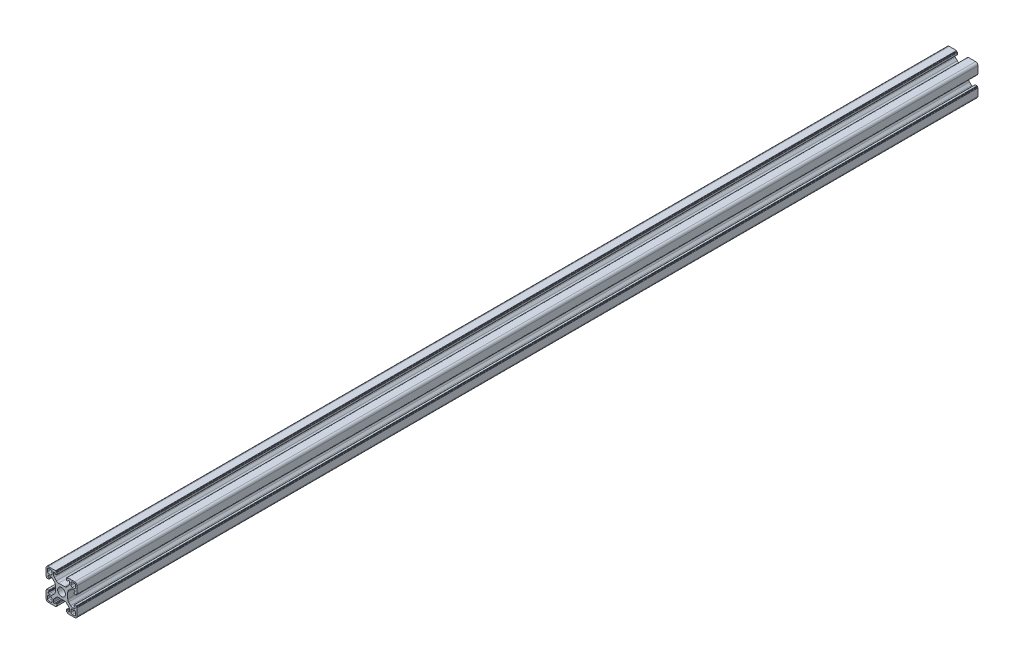
SolidWorks part; units mm, degrees
material "1060 Сплав"
ref_plane "Спереди" through (0, 0, 0) normal (0, 0, 1) x (1, 0, 0)
ref_plane "Сверху" through (0, 0, 0) normal (0, 1, 0) x (1, 0, 0)
ref_plane "Справа" through (0, 0, 0) normal (1, 0, 0) x (0, 0, -1)
sketch "Эскиз1" plane through (0, 0, 0) normal (0, 0, 1) x (1, 0, 0)
  line L0 (-22.0052, 70.3096) -> (-25.0052, 67.3096) construction
  line L1 (-31.1052, 65.2096) -> (-29.2064, 65.2096)
  line L2 (-31.1052, 61.2096) -> (-21.1052, 71.2096) construction
  line L3 (-23.5052, 68.8096) -> (-25.0052, 70.3096) construction
  line L4 (-27.7922, 65.7954) -> (-26.4909, 67.0967)
  line L5 (-24.2052, 67.3096) -> (-22.8052, 67.3096)
  line L6 (-25.0052, 68.1096) -> (-25.0052, 69.5096)
  line L7 (-22.8052, 70.3096) -> (-24.2052, 70.3096)
  line L8 (-25.9052, 69.4096) -> (-25.9052, 68.5109)
  line L9 (-27.3419, 69.2829) -> (-26.8616, 69.7632)
  line L10 (-27.9052, 70.7587) -> (-27.4052, 70.7587)
  line L11 (-27.5187, 69.2096) -> (-27.8052, 69.2096)
  line L12 (-26.508, 69.9096) -> (-26.4052, 69.9096)
  line L13 (-27.4052, 71.0596) -> (-27.4052, 70.7587)
  line L14 (-28.0552, 70.6087) -> (-28.0552, 69.4596)
  line L15 (-22.6052, 71.2096) -> (-27.2552, 71.2096)
  line L16 (-22.0052, 69.5096) -> (-22.0052, 68.1096)
  line L17 (-21.1052, 69.7096) -> (-21.1052, 65.0596)
  line L18 (-21.7061, 64.2596) -> (-22.8552, 64.2596)
  line L19 (-21.2552, 64.9096) -> (-21.5561, 64.9096)
  line L20 (-22.4052, 65.8068) -> (-22.4052, 65.9096)
  line L21 (-23.1052, 64.7961) -> (-23.1052, 64.5096)
  line L22 (-21.5561, 64.4096) -> (-21.5561, 64.9096)
  line L23 (-23.0319, 64.9729) -> (-22.5516, 65.4532)
  line L24 (-22.9052, 66.4096) -> (-23.8039, 66.4096)
  line L25 (-26.5194, 64.5226) -> (-25.2181, 65.8239)
  line L26 (-27.1052, 61.2096) -> (-27.1052, 63.1084)
  line L27 (-27.1052, 61.2096) -> (-27.1052, 59.3109)
  line L28 (-26.5194, 57.8967) -> (-25.2181, 56.5954)
  line L29 (-25.0052, 54.3096) -> (-25.0052, 52.9096)
  line L30 (-24.2052, 55.1096) -> (-22.8052, 55.1096)
  line L31 (-22.0052, 52.9096) -> (-22.0052, 54.3096)
  line L32 (-22.9052, 56.0096) -> (-23.8039, 56.0096)
  line L33 (-23.0319, 57.4464) -> (-22.5516, 56.9661)
  line L34 (-21.5561, 58.0096) -> (-21.5561, 57.5096)
  line L35 (-23.1052, 57.6232) -> (-23.1052, 57.9096)
  line L36 (-22.4052, 56.6125) -> (-22.4052, 56.5096)
  line L37 (-21.2552, 57.5096) -> (-21.5561, 57.5096)
  line L38 (-21.7061, 58.1596) -> (-22.8552, 58.1596)
  line L39 (-21.1052, 52.7096) -> (-21.1052, 57.3596)
  line L40 (-22.8052, 52.1096) -> (-24.2052, 52.1096)
  line L41 (-22.6052, 51.2096) -> (-27.2552, 51.2096)
  line L42 (-28.0552, 51.8106) -> (-28.0552, 52.9596)
  line L43 (-27.4052, 51.3596) -> (-27.4052, 51.6606)
  line L44 (-26.508, 52.5096) -> (-26.4052, 52.5096)
  line L45 (-27.5187, 53.2096) -> (-27.8052, 53.2096)
  line L46 (-27.9052, 51.6606) -> (-27.4052, 51.6606)
  line L47 (-27.3419, 53.1364) -> (-26.8616, 52.6561)
  line L48 (-25.9052, 53.0096) -> (-25.9052, 53.9084)
  line L49 (-27.7922, 56.6239) -> (-26.4909, 55.3226)
  line L50 (-31.1052, 57.2096) -> (-29.2064, 57.2096)
  line L51 (-22.0052, 52.1096) -> (-25.0052, 55.1096) construction
  line L52 (-31.1052, 61.2096) -> (-21.1052, 51.2096) construction
  line L53 (-23.5052, 53.6096) -> (-22.0052, 55.1096) construction
  line L54 (-31.1052, 57.2096) -> (-33.0039, 57.2096)
  line L55 (-34.4181, 56.6239) -> (-35.7194, 55.3226)
  line L56 (-38.0052, 55.1096) -> (-39.4052, 55.1096)
  line L57 (-37.2052, 54.3096) -> (-37.2052, 52.9096)
  line L58 (-39.4052, 52.1096) -> (-38.0052, 52.1096)
  line L59 (-36.3052, 53.0096) -> (-36.3052, 53.9084)
  line L60 (-34.8684, 53.1364) -> (-35.3487, 52.6561)
  line L61 (-34.3052, 51.6606) -> (-34.8052, 51.6606)
  line L62 (-34.6916, 53.2096) -> (-34.4052, 53.2096)
  line L63 (-35.7023, 52.5096) -> (-35.8052, 52.5096)
  line L64 (-34.8052, 51.3596) -> (-34.8052, 51.6606)
  line L65 (-34.1552, 51.8106) -> (-34.1552, 52.9596)
  line L66 (-39.6052, 51.2096) -> (-34.9552, 51.2096)
  line L67 (-40.2052, 52.9096) -> (-40.2052, 54.3096)
  line L68 (-41.1052, 52.7096) -> (-41.1052, 57.3596)
  line L69 (-40.5042, 58.1596) -> (-39.3552, 58.1596)
  line L70 (-40.9552, 57.5096) -> (-40.6542, 57.5096)
  line L71 (-39.8052, 56.6125) -> (-39.8052, 56.5096)
  line L72 (-39.1052, 57.6232) -> (-39.1052, 57.9096)
  line L73 (-40.6542, 58.0096) -> (-40.6542, 57.5096)
  line L74 (-39.1784, 57.4464) -> (-39.6587, 56.9661)
  line L75 (-39.3052, 56.0096) -> (-38.4064, 56.0096)
  line L76 (-35.6909, 57.8967) -> (-36.9922, 56.5954)
  line L77 (-35.1052, 61.2096) -> (-35.1052, 59.3109)
  line L78 (-40.2052, 52.1096) -> (-37.2052, 55.1096) construction
  line L79 (-31.1052, 61.2096) -> (-41.1052, 51.2096) construction
  line L80 (-38.7052, 53.6096) -> (-37.2052, 52.1096) construction
  line L81 (-35.1052, 61.2096) -> (-35.1052, 63.1084)
  line L82 (-35.6909, 64.5226) -> (-36.9922, 65.8239)
  line L83 (-37.2052, 68.1096) -> (-37.2052, 69.5096)
  line L84 (-38.0052, 67.3096) -> (-39.4052, 67.3096)
  line L85 (-40.2052, 69.5096) -> (-40.2052, 68.1096)
  line L86 (-39.3052, 66.4096) -> (-38.4064, 66.4096)
  line L87 (-39.1784, 64.9729) -> (-39.6587, 65.4532)
  line L88 (-40.6542, 64.4096) -> (-40.6542, 64.9096)
  line L89 (-39.1052, 64.7961) -> (-39.1052, 64.5096)
  line L90 (-39.8052, 65.8068) -> (-39.8052, 65.9096)
  line L91 (-40.9552, 64.9096) -> (-40.6542, 64.9096)
  line L92 (-40.5042, 64.2596) -> (-39.3552, 64.2596)
  line L93 (-41.1052, 69.7096) -> (-41.1052, 65.0596)
  line L94 (-39.4052, 70.3096) -> (-38.0052, 70.3096)
  line L95 (-39.6052, 71.2096) -> (-34.9552, 71.2096)
  line L96 (-34.1552, 70.6087) -> (-34.1552, 69.4596)
  line L97 (-34.8052, 71.0596) -> (-34.8052, 70.7587)
  line L98 (-35.7023, 69.9096) -> (-35.8052, 69.9096)
  line L99 (-34.6916, 69.2096) -> (-34.4052, 69.2096)
  line L100 (-34.3052, 70.7587) -> (-34.8052, 70.7587)
  line L101 (-34.8684, 69.2829) -> (-35.3487, 69.7632)
  line L102 (-36.3052, 69.4096) -> (-36.3052, 68.5109)
  line L103 (-34.4181, 65.7954) -> (-35.7194, 67.0967)
  line L104 (-31.1052, 65.2096) -> (-33.0039, 65.2096)
  line L105 (-42.8692, 61.2096) -> (-19.6008, 61.2096) construction
  line L106 (-40.2052, 70.3096) -> (-37.2052, 67.3096) construction
  line L107 (-31.1052, 49.1232) -> (-31.1052, 71.9286) construction
  line L108 (-31.1052, 61.2096) -> (-41.1052, 71.2096) construction
  line L109 (-38.7052, 68.8096) -> (-40.2052, 67.3096) construction
  arc A0 (-22.0052, 69.5096) -> (-22.8052, 70.3096) centre (-22.8052, 69.5096) ccw
  arc A1 (-24.2052, 70.3096) -> (-25.0052, 69.5096) centre (-24.2052, 69.5096) ccw
  arc A2 (-24.2052, 67.3096) -> (-25.0052, 68.1096) centre (-24.2052, 68.1096) cw
  arc A3 (-22.6052, 71.2096) -> (-21.1052, 69.7096) centre (-22.6052, 69.7096) cw
  arc A4 (-27.9052, 70.7587) -> (-28.0552, 70.6087) centre (-27.9052, 70.6087) ccw
  arc A5 (-27.2552, 71.2096) -> (-27.4052, 71.0596) centre (-27.2552, 71.0596) ccw
  arc A6 (-27.5187, 69.2096) -> (-27.3419, 69.2829) centre (-27.5187, 69.4596) ccw
  arc A7 (-27.8052, 69.2096) -> (-28.0552, 69.4596) centre (-27.8052, 69.4596) cw
  arc A8 (-26.8616, 69.7632) -> (-26.508, 69.9096) centre (-26.508, 69.4096) cw
  arc A9 (-26.4052, 69.9096) -> (-25.9052, 69.4096) centre (-26.4052, 69.4096) cw
  arc A10 (-28.6052, 61.2096) -> (-31.1052, 63.7096) centre (-31.1052, 61.2096) ccw
  arc A11 (-29.2064, 65.2096) -> (-27.7922, 65.7954) centre (-29.2064, 67.2096) ccw
  arc A12 (-25.9052, 68.5109) -> (-26.4909, 67.0967) centre (-27.9052, 68.5109) cw
  arc A13 (-22.0052, 68.1096) -> (-22.8052, 67.3096) centre (-22.8052, 68.1096) cw
  arc A14 (-22.4052, 65.9096) -> (-22.9052, 66.4096) centre (-22.9052, 65.9096) ccw
  arc A15 (-22.5516, 65.4532) -> (-22.4052, 65.8068) centre (-22.9052, 65.8068) ccw
  arc A16 (-23.1052, 64.5096) -> (-22.8552, 64.2596) centre (-22.8552, 64.5096) ccw
  arc A17 (-23.1052, 64.7961) -> (-23.0319, 64.9729) centre (-22.8552, 64.7961) cw
  arc A18 (-21.1052, 65.0596) -> (-21.2552, 64.9096) centre (-21.2552, 65.0596) cw
  arc A19 (-21.5561, 64.4096) -> (-21.7061, 64.2596) centre (-21.7061, 64.4096) cw
  arc A20 (-23.8039, 66.4096) -> (-25.2181, 65.8239) centre (-23.8039, 64.4096) ccw
  arc A21 (-27.1052, 63.1084) -> (-26.5194, 64.5226) centre (-25.1052, 63.1084) cw
  arc A22 (-22.8052, 52.1096) -> (-22.0052, 52.9096) centre (-22.8052, 52.9096) ccw
  arc A23 (-22.0052, 54.3096) -> (-22.8052, 55.1096) centre (-22.8052, 54.3096) ccw
  arc A24 (-25.0052, 54.3096) -> (-24.2052, 55.1096) centre (-24.2052, 54.3096) cw
  arc A25 (-21.1052, 52.7096) -> (-22.6052, 51.2096) centre (-22.6052, 52.7096) cw
  arc A26 (-21.5561, 58.0096) -> (-21.7061, 58.1596) centre (-21.7061, 58.0096) ccw
  arc A27 (-21.1052, 57.3596) -> (-21.2552, 57.5096) centre (-21.2552, 57.3596) ccw
  arc A28 (-23.1052, 57.6232) -> (-23.0319, 57.4464) centre (-22.8552, 57.6232) ccw
  arc A29 (-23.1052, 57.9096) -> (-22.8552, 58.1596) centre (-22.8552, 57.9096) cw
  arc A30 (-22.5516, 56.9661) -> (-22.4052, 56.6125) centre (-22.9052, 56.6125) cw
  arc A31 (-22.4052, 56.5096) -> (-22.9052, 56.0096) centre (-22.9052, 56.5096) cw
  arc A32 (-31.1052, 58.7096) -> (-28.6052, 61.2096) centre (-31.1052, 61.2096) ccw
  arc A33 (-27.1052, 59.3109) -> (-26.5194, 57.8967) centre (-25.1052, 59.3109) ccw
  arc A34 (-23.8039, 56.0096) -> (-25.2181, 56.5954) centre (-23.8039, 58.0096) cw
  arc A35 (-24.2052, 52.1096) -> (-25.0052, 52.9096) centre (-24.2052, 52.9096) cw
  arc A36 (-26.4052, 52.5096) -> (-25.9052, 53.0096) centre (-26.4052, 53.0096) ccw
  arc A37 (-26.8616, 52.6561) -> (-26.508, 52.5096) centre (-26.508, 53.0096) ccw
  arc A38 (-27.8052, 53.2096) -> (-28.0552, 52.9596) centre (-27.8052, 52.9596) ccw
  arc A39 (-27.5187, 53.2096) -> (-27.3419, 53.1364) centre (-27.5187, 52.9596) cw
  arc A40 (-27.2552, 51.2096) -> (-27.4052, 51.3596) centre (-27.2552, 51.3596) cw
  arc A41 (-27.9052, 51.6606) -> (-28.0552, 51.8106) centre (-27.9052, 51.8106) cw
  arc A42 (-25.9052, 53.9084) -> (-26.4909, 55.3226) centre (-27.9052, 53.9084) ccw
  arc A43 (-29.2064, 57.2096) -> (-27.7922, 56.6239) centre (-29.2064, 55.2096) cw
  arc A44 (-40.2052, 52.9096) -> (-39.4052, 52.1096) centre (-39.4052, 52.9096) ccw
  arc A45 (-38.0052, 52.1096) -> (-37.2052, 52.9096) centre (-38.0052, 52.9096) ccw
  arc A46 (-38.0052, 55.1096) -> (-37.2052, 54.3096) centre (-38.0052, 54.3096) cw
  arc A47 (-39.6052, 51.2096) -> (-41.1052, 52.7096) centre (-39.6052, 52.7096) cw
  arc A48 (-34.3052, 51.6606) -> (-34.1552, 51.8106) centre (-34.3052, 51.8106) ccw
  arc A49 (-34.9552, 51.2096) -> (-34.8052, 51.3596) centre (-34.9552, 51.3596) ccw
  arc A50 (-34.6916, 53.2096) -> (-34.8684, 53.1364) centre (-34.6916, 52.9596) ccw
  arc A51 (-34.4052, 53.2096) -> (-34.1552, 52.9596) centre (-34.4052, 52.9596) cw
  arc A52 (-35.3487, 52.6561) -> (-35.7023, 52.5096) centre (-35.7023, 53.0096) cw
  arc A53 (-35.8052, 52.5096) -> (-36.3052, 53.0096) centre (-35.8052, 53.0096) cw
  arc A54 (-33.6052, 61.2096) -> (-31.1052, 58.7096) centre (-31.1052, 61.2096) ccw
  arc A55 (-33.0039, 57.2096) -> (-34.4181, 56.6239) centre (-33.0039, 55.2096) ccw
  arc A56 (-36.3052, 53.9084) -> (-35.7194, 55.3226) centre (-34.3052, 53.9084) cw
  arc A57 (-40.2052, 54.3096) -> (-39.4052, 55.1096) centre (-39.4052, 54.3096) cw
  arc A58 (-39.8052, 56.5096) -> (-39.3052, 56.0096) centre (-39.3052, 56.5096) ccw
  arc A59 (-39.6587, 56.9661) -> (-39.8052, 56.6125) centre (-39.3052, 56.6125) ccw
  arc A60 (-39.1052, 57.9096) -> (-39.3552, 58.1596) centre (-39.3552, 57.9096) ccw
  arc A61 (-39.1052, 57.6232) -> (-39.1784, 57.4464) centre (-39.3552, 57.6232) cw
  arc A62 (-41.1052, 57.3596) -> (-40.9552, 57.5096) centre (-40.9552, 57.3596) cw
  arc A63 (-40.6542, 58.0096) -> (-40.5042, 58.1596) centre (-40.5042, 58.0096) cw
  arc A64 (-38.4064, 56.0096) -> (-36.9922, 56.5954) centre (-38.4064, 58.0096) ccw
  arc A65 (-35.1052, 59.3109) -> (-35.6909, 57.8967) centre (-37.1052, 59.3109) cw
  arc A66 (-39.4052, 70.3096) -> (-40.2052, 69.5096) centre (-39.4052, 69.5096) ccw
  arc A67 (-40.2052, 68.1096) -> (-39.4052, 67.3096) centre (-39.4052, 68.1096) ccw
  arc A68 (-37.2052, 68.1096) -> (-38.0052, 67.3096) centre (-38.0052, 68.1096) cw
  arc A69 (-41.1052, 69.7096) -> (-39.6052, 71.2096) centre (-39.6052, 69.7096) cw
  arc A70 (-40.6542, 64.4096) -> (-40.5042, 64.2596) centre (-40.5042, 64.4096) ccw
  arc A71 (-41.1052, 65.0596) -> (-40.9552, 64.9096) centre (-40.9552, 65.0596) ccw
  arc A72 (-39.1052, 64.7961) -> (-39.1784, 64.9729) centre (-39.3552, 64.7961) ccw
  arc A73 (-39.1052, 64.5096) -> (-39.3552, 64.2596) centre (-39.3552, 64.5096) cw
  arc A74 (-39.6587, 65.4532) -> (-39.8052, 65.8068) centre (-39.3052, 65.8068) cw
  arc A75 (-39.8052, 65.9096) -> (-39.3052, 66.4096) centre (-39.3052, 65.9096) cw
  arc A76 (-31.1052, 63.7096) -> (-33.6052, 61.2096) centre (-31.1052, 61.2096) ccw
  arc A77 (-35.1052, 63.1084) -> (-35.6909, 64.5226) centre (-37.1052, 63.1084) ccw
  arc A78 (-38.4064, 66.4096) -> (-36.9922, 65.8239) centre (-38.4064, 64.4096) cw
  arc A79 (-38.0052, 70.3096) -> (-37.2052, 69.5096) centre (-38.0052, 69.5096) cw
  arc A80 (-35.8052, 69.9096) -> (-36.3052, 69.4096) centre (-35.8052, 69.4096) ccw
  arc A81 (-35.3487, 69.7632) -> (-35.7023, 69.9096) centre (-35.7023, 69.4096) ccw
  arc A82 (-34.4052, 69.2096) -> (-34.1552, 69.4596) centre (-34.4052, 69.4596) ccw
  arc A83 (-34.6916, 69.2096) -> (-34.8684, 69.2829) centre (-34.6916, 69.4596) cw
  arc A84 (-34.9552, 71.2096) -> (-34.8052, 71.0596) centre (-34.9552, 71.0596) cw
  arc A85 (-34.3052, 70.7587) -> (-34.1552, 70.6087) centre (-34.3052, 70.6087) cw
  arc A86 (-36.3052, 68.5109) -> (-35.7194, 67.0967) centre (-34.3052, 68.5109) ccw
  arc A87 (-33.0039, 65.2096) -> (-34.4181, 65.7954) centre (-33.0039, 67.2096) cw
  point P0 (-31.1052, 61.2096)
  point P9 (-31.1052, 61.2096)
  point P40 (-22.4052, 64.9096)
  point P93 (-27.4052, 52.5096)
  point P144 (-27.4052, 69.9096)
  point P152 (-22.4052, 57.5096)
  point P153 (-31.1052, 57.2854)
  point P154 (-31.1052, 61.2096)
  point P189 (-39.8052, 57.5096)
  point P228 (-34.8052, 52.5096)
  point P229 (-35.0294, 61.2096)
  point P230 (-31.1052, 61.2096)
  point P268 (-34.8052, 69.9096)
  point P273 (-27.1809, 61.2096)
  point P306 (-39.8052, 64.9096)
  point P307 (-31.1052, 65.1339)
  point P309 (-31.1052, 61.2096)
  dimension "D3" = 5
  dimension "D6" = 2
  dimension "D1" = 2
  dimension "D2" = 6
  dimension "D4" = 4
  dimension "D5" = 0.9
extrude "Бобышка-Вытянуть1" add sketch "Эскиз1" along normal blind 580
